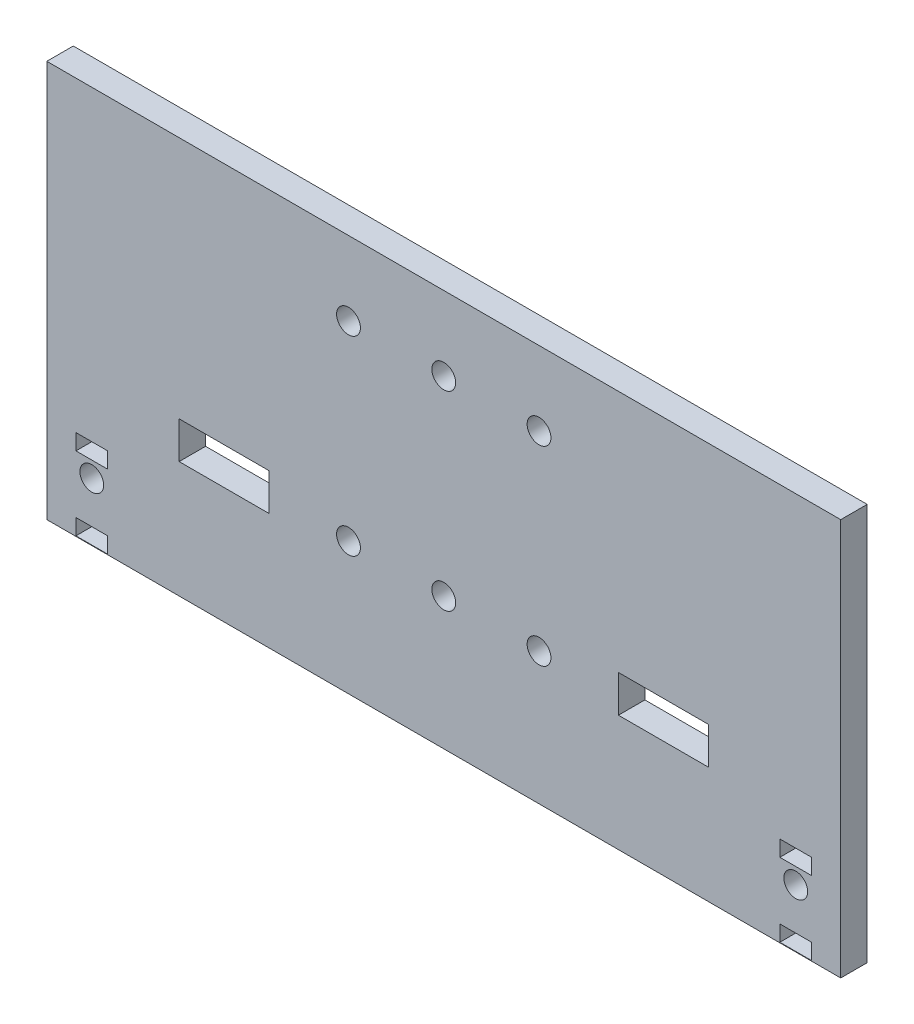
SolidWorks part; units mm, degrees
ref_plane "Plan de face" through (0, 0, 0) normal (0, 0, 1) x (1, 0, 0)
ref_plane "Plan de dessus" through (0, 0, 0) normal (0, 1, 0) x (1, 0, 0)
ref_plane "Plan de droite" through (0, 0, 0) normal (1, 0, 0) x (0, 0, -1)
sketch "Esquisse1" plane through (0, 0, 0) normal (0, 0, 1) x (1, 0, 0)
  line L0 (8.5, -64) -> (141.5, -64) construction
  line L1 (0, 0) -> (150, 0)
  line L2 (0, 0) -> (0, -75)
  line L3 (0, -75) -> (150, -75)
  line L4 (150, 0) -> (150, -75)
  line L5 (75, -14) -> (75, -50) construction
  line L7 (57, -14) -> (93, -14) construction
  line L8 (57, -14) -> (57, -50) construction
  line L9 (57, -50) -> (93, -50) construction
  line L10 (93, -14) -> (93, -50) construction
  line L11 (57, -14) -> (93, -50) construction
  line L12 (57, -50) -> (93, -14) construction
  line L13 (5.5, -58) -> (11.5, -58)
  line L14 (5.5, -58) -> (5.5, -61)
  line L15 (5.5, -61) -> (11.5, -61)
  line L16 (11.5, -58) -> (11.5, -61)
  line L17 (5.5, -71.9) -> (11.5, -71.9)
  line L18 (5.5, -71.9) -> (5.5, -74.9)
  line L19 (5.5, -74.9) -> (11.5, -74.9)
  line L20 (11.5, -71.9) -> (11.5, -74.9)
  line L21 (138.5, -58) -> (144.5, -58)
  line L22 (138.5, -58) -> (138.5, -61)
  line L23 (138.5, -61) -> (144.5, -61)
  line L24 (144.5, -58) -> (144.5, -61)
  line L25 (138.5, -71.9) -> (144.5, -71.9)
  line L26 (138.5, -71.9) -> (138.5, -74.9)
  line L27 (138.5, -74.9) -> (144.5, -74.9)
  line L28 (144.5, -71.9) -> (144.5, -74.9)
  line L29 (25, -46) -> (42, -46)
  line L30 (25, -46) -> (25, -53)
  line L31 (25, -53) -> (42, -53)
  line L32 (42, -46) -> (42, -53)
  line L33 (108, -46) -> (125, -46)
  line L34 (108, -46) -> (108, -53)
  line L35 (108, -53) -> (125, -53)
  line L36 (125, -46) -> (125, -53)
  circle A1 centre (8.5, -64) radius 2.25
  circle A2 centre (141.5, -64) radius 2.25
  circle A4 centre (57, -14) radius 2.25
  circle A5 centre (93, -14) radius 2.25
  circle A6 centre (93, -50) radius 2.25
  circle A7 centre (57, -50) radius 2.25
  circle A8 centre (75, -14) radius 2.25
  circle A10 centre (75, -50) radius 2.25
  point P12 (75, -32)
  point P26 (5.5, -59.5)
  point P39 (144.5, -59.5)
  point P48 (116.5, -53)
  dimension "D3" = 32
  dimension "D4" = 6
  dimension "D6" = 4.5
  dimension "D11" = 4.5
  dimension "D1" = 150
  dimension "D2" = 75
  dimension "D5" = 75
  dimension "D7" = 8.5
  dimension "D8" = 11
  dimension "D9" = 8.5
  dimension "D10" = 3
  dimension "D12" = 36
  dimension "D13" = 36
  dimension "D14" = 17
  dimension "D15" = 5.5
  dimension "D16" = 5.5
  dimension "D17" = 5.5
  dimension "D18" = 5.5
  dimension "D19" = 17
  dimension "D20" = 0.1
  dimension "D21" = 0.1
  dimension "D22" = 17
  dimension "D23" = 7
  dimension "D24" = 25
  dimension "D25" = 25
  dimension "D26" = 22
  dimension "D27" = 22
extrude "Boss.-Extru.1" add sketch "Esquisse1" along normal blind 5
